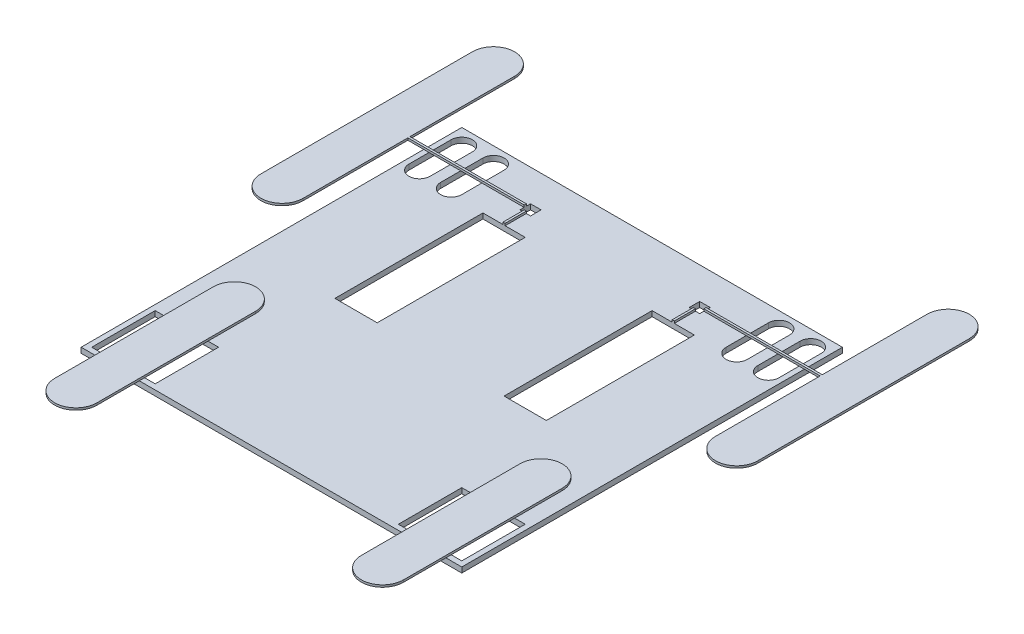
SolidWorks part; units mm, degrees
ref_plane "Front Plane" through (0, 0, 0) normal (0, 0, 1) x (1, 0, 0)
ref_plane "Top Plane" through (0, 0, 0) normal (0, 1, 0) x (1, 0, 0)
ref_plane "Right Plane" through (0, 0, 0) normal (1, 0, 0) x (0, 0, -1)
sketch "Sketch2" plane through (0, 0, 0) normal (0, 1, 0) x (1, 0, 0)
  line L0 (19.05, 438.15) -> (19.05, 387.35) construction
  line L1 (0, 0) -> (457.2, 0)
  line L2 (0, 0) -> (0, 457.2)
  line L3 (0, 457.2) -> (457.2, 457.2)
  line L4 (457.2, 0) -> (457.2, 457.2)
  line L5 (31.75, 438.15) -> (31.75, 387.35)
  line L6 (6.35, 438.15) -> (6.35, 387.35)
  line L7 (228.6, 0) -> (228.6, 457.2) construction
  line L10 (57.15, 438.15) -> (57.15, 387.35) construction
  line L11 (69.85, 438.15) -> (69.85, 387.35)
  line L12 (44.45, 438.15) -> (44.45, 387.35)
  line L13 (0, 228.6) -> (457.2, 228.6) construction
  line L14 (438.15, 438.15) -> (438.15, 387.35) construction
  line L15 (425.45, 438.15) -> (425.45, 387.35)
  line L16 (450.85, 438.15) -> (450.85, 387.35)
  line L17 (400.05, 438.15) -> (400.05, 387.35) construction
  line L18 (387.35, 438.15) -> (387.35, 387.35)
  line L19 (412.75, 438.15) -> (412.75, 387.35)
  line L20 (336.55, 406.4) -> (323.85, 406.4)
  line L23 (101.6, 381) -> (152.4, 381)
  line L26 (101.6, 381) -> (101.6, 203.2)
  line L29 (101.6, 203.2) -> (152.4, 203.2)
  line L32 (152.4, 381) -> (152.4, 203.2)
  line L33 (120.65, 419.1) -> (133.35, 419.1)
  line L34 (120.65, 419.1) -> (120.65, 406.4)
  line L35 (120.65, 406.4) -> (133.35, 406.4)
  line L36 (133.35, 419.1) -> (133.35, 406.4)
  line L37 (323.85, 419.1) -> (323.85, 406.4)
  line L38 (336.55, 419.1) -> (336.55, 406.4)
  line L39 (336.55, 419.1) -> (323.85, 419.1)
  line L40 (355.6, 203.2) -> (304.8, 203.2)
  line L41 (355.6, 381) -> (355.6, 203.2)
  line L42 (304.8, 381) -> (304.8, 203.2)
  line L43 (355.6, 381) -> (304.8, 381)
  line L44 (450.85, 82.55) -> (374.65, 82.55)
  line L45 (6.35, 6.35) -> (82.55, 6.35)
  line L46 (6.35, 6.35) -> (6.35, 82.55)
  line L47 (6.35, 82.55) -> (82.55, 82.55)
  line L48 (82.55, 6.35) -> (82.55, 82.55)
  line L49 (450.85, 6.35) -> (450.85, 82.55)
  line L50 (450.85, 6.35) -> (374.65, 6.35)
  line L51 (374.65, 6.35) -> (374.65, 82.55)
  arc A0 (31.75, 438.15) -> (6.35, 438.15) centre (19.05, 438.15) ccw
  arc A1 (6.35, 387.35) -> (31.75, 387.35) centre (19.05, 387.35) ccw
  arc A4 (69.85, 438.15) -> (44.45, 438.15) centre (57.15, 438.15) ccw
  arc A5 (44.45, 387.35) -> (69.85, 387.35) centre (57.15, 387.35) ccw
  arc A6 (425.45, 438.15) -> (450.85, 438.15) centre (438.15, 438.15) cw
  arc A7 (450.85, 387.35) -> (425.45, 387.35) centre (438.15, 387.35) cw
  arc A8 (387.35, 438.15) -> (412.75, 438.15) centre (400.05, 438.15) cw
  arc A9 (412.75, 387.35) -> (387.35, 387.35) centre (400.05, 387.35) cw
  point P7 (19.05, 412.75)
  point P21 (57.15, 412.75)
  point P29 (438.15, 412.75)
  point P36 (400.05, 412.75)
  dimension "D3" = 12.7
  dimension "D9" = 12.7
  dimension "D1" = 457.2
  dimension "D2" = 457.2
  dimension "D4" = 50.8
  dimension "D5" = 19.05
  dimension "D6" = 19.05
  dimension "D7" = 50.8
  dimension "D8" = 19.05
  dimension "D10" = 38.1
  dimension "D11" = 12.7
  dimension "D12" = 12.7
  dimension "D13" = 6.35
  dimension "D14" = 50.8
  dimension "D15" = 177.8
  dimension "D16" = 25.4
  dimension "D17" = 50.8
  dimension "D18" = 31.75
  dimension "D19" = 76.2
  dimension "D20" = 76.2
  dimension "D21" = 6.35
  dimension "D22" = 6.35
extrude "Boss-Extrude1" add sketch "Sketch2" along normal blind 6.35
sketch "Sketch3" plane through (0, 6.35, 0) normal (0, 1, 0) x (1, 0, 0)
  line L0 (120.65, 419.1) -> (120.65, 406.4) construction
  line L1 (-44.45, 539.75) -> (-44.45, 285.75) construction
  line L2 (120.65, 411.48) -> (-19.05, 411.48)
  line L3 (-19.05, 539.75) -> (-19.05, 414.02)
  line L4 (-69.85, 539.75) -> (-69.85, 285.75)
  line L5 (120.65, 411.48) -> (120.65, 414.02)
  line L6 (120.65, 414.02) -> (-19.05, 414.02)
  line L8 (120.65, 406.4) -> (133.35, 406.4) construction
  line L9 (125.73, 406.4) -> (128.27, 406.4)
  line L10 (125.73, 406.4) -> (125.73, 381)
  line L11 (125.73, 381) -> (128.27, 381)
  line L12 (128.27, 406.4) -> (128.27, 381)
  line L13 (152.4, 381) -> (101.6, 381) construction
  line L14 (133.35, 419.1) -> (120.65, 419.1) construction
  line L15 (133.35, 406.4) -> (133.35, 419.1) construction
  line L16 (44.45, 139.7) -> (44.45, -50.8) construction
  line L17 (0, 0) -> (457.2, 0) construction
  line L18 (228.6, 457.2) -> (228.6, 0) construction
  line L19 (457.2, 457.2) -> (0, 457.2) construction
  line L20 (0, 228.6) -> (457.2, 228.6) construction
  line L21 (0, 457.2) -> (0, 0) construction
  line L22 (457.2, 0) -> (457.2, 457.2) construction
  line L23 (331.47, 381) -> (328.93, 381)
  line L24 (331.47, 406.4) -> (331.47, 381)
  line L25 (328.93, 406.4) -> (328.93, 381)
  line L26 (331.47, 406.4) -> (328.93, 406.4)
  line L27 (336.55, 411.48) -> (336.55, 414.02)
  line L28 (336.55, 411.48) -> (476.25, 411.48)
  line L29 (336.55, 414.02) -> (476.25, 414.02)
  line L30 (501.65, 539.75) -> (501.65, 285.75) construction
  line L31 (476.25, 539.75) -> (476.25, 414.02)
  line L32 (527.05, 539.75) -> (527.05, 285.75)
  line L33 (69.85, 139.7) -> (69.85, -50.8)
  line L34 (19.05, 139.7) -> (19.05, -50.8)
  line L35 (82.55, 82.55) -> (6.35, 82.55) construction
  line L36 (6.35, 82.55) -> (6.35, 6.35) construction
  line L37 (412.75, 139.7) -> (412.75, -50.8) construction
  line L38 (387.35, 139.7) -> (387.35, -50.8)
  line L39 (438.15, 139.7) -> (438.15, -50.8)
  line L40 (-19.05, 411.48) -> (-19.05, 285.75)
  line L41 (476.25, 411.48) -> (476.25, 285.75)
  arc A0 (-19.05, 539.75) -> (-69.85, 539.75) centre (-44.45, 539.75) ccw
  arc A1 (-69.85, 285.75) -> (-19.05, 285.75) centre (-44.45, 285.75) ccw
  arc A2 (476.25, 539.75) -> (527.05, 539.75) centre (501.65, 539.75) cw
  arc A3 (527.05, 285.75) -> (476.25, 285.75) centre (501.65, 285.75) cw
  arc A4 (69.85, 139.7) -> (19.05, 139.7) centre (44.45, 139.7) ccw
  arc A5 (19.05, -50.8) -> (69.85, -50.8) centre (44.45, -50.8) ccw
  arc A6 (387.35, 139.7) -> (438.15, 139.7) centre (412.75, 139.7) cw
  arc A7 (438.15, -50.8) -> (387.35, -50.8) centre (412.75, -50.8) cw
  point P20 (-44.45, 412.75)
  point P47 (501.65, 412.75)
  point P54 (44.45, 44.45)
  point P65 (412.75, 44.45)
  dimension "D8" = 25.4
  dimension "D10" = 25.4
  dimension "D13" = 190.5
  dimension "D1" = 139.7
  dimension "D2" = 5.08
  dimension "D3" = 5.08
  dimension "D4" = 5.08
  dimension "D5" = 5.08
  dimension "D6" = 254
  dimension "D7" = 412.75
  dimension "D11" = 38.1
  dimension "D12" = 38.1
extrude "Boss-Extrude2" add sketch "Sketch3" along normal blind 2.54
